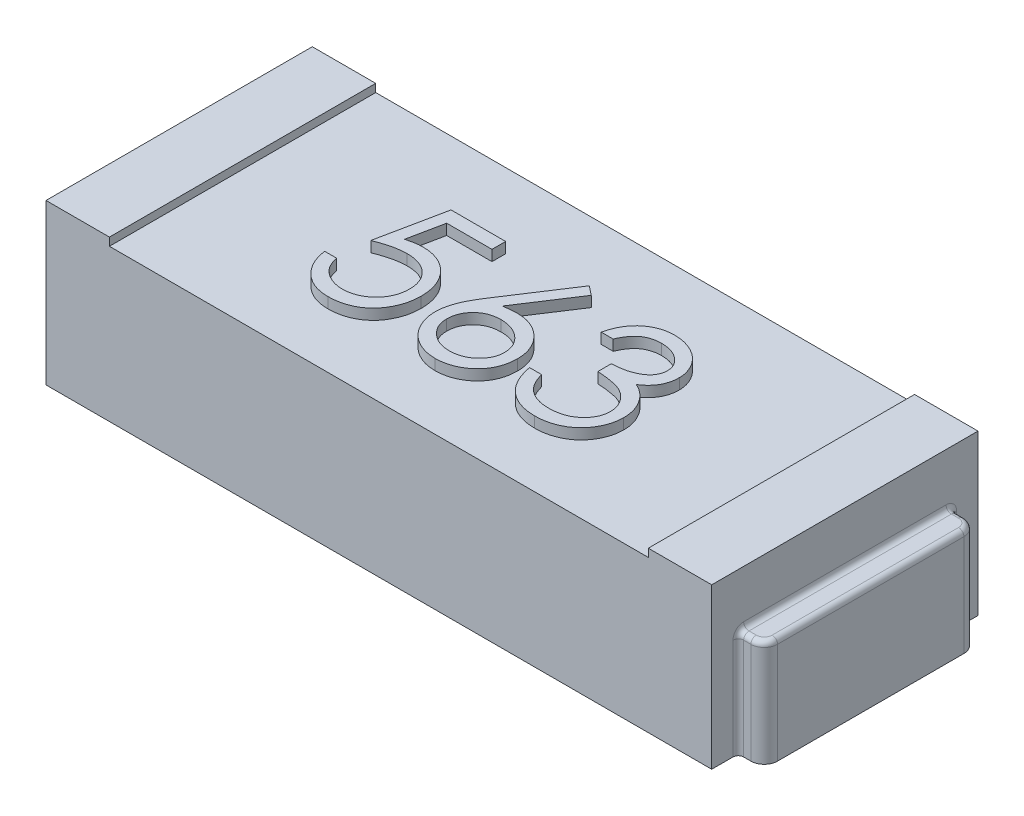
SolidWorks part; units mm, degrees
ref_plane "Plan de face" through (0, 0, 0) normal (0, 0, 1) x (1, 0, 0)
ref_plane "Plan de dessus" through (0, 0, 0) normal (0, 1, 0) x (1, 0, 0)
ref_plane "Plan de droite" through (0, 0, 0) normal (1, 0, 0) x (0, 0, -1)
sketch "Esquisse1" plane through (0, 0, 0) normal (0, 1, 0) x (1, 0, 0)
  line L1 (1.25, -0.5) -> (-1.25, -0.5)
  line L2 (1.25, -0.5) -> (1.25, 0.5)
  line L3 (1.25, 0.5) -> (-1.25, 0.5)
  line L4 (-1.25, -0.5) -> (-1.25, 0.5)
  line L5 (1.25, -0.5) -> (-1.25, 0.5) construction
  line L6 (1.25, 0.5) -> (-1.25, -0.5) construction
  point P0 (0, 0)
  dimension "D1" = 2.5
  dimension "D2" = 1
extrude "Boss.-Extru.1" add sketch "Esquisse1" along normal blind 0.6
sketch "Esquisse2" plane through (0, 0.6, 0) normal (0, 1, 0) x (1, 0, 0)
  line L0 (1.25, 0.5) -> (-1.25, 0.5) construction
  line L1 (1.0118, -0.5) -> (-1.0118, -0.5)
  line L2 (1.0118, -0.5) -> (1.0118, 0.5)
  line L3 (1.0118, 0.5) -> (-1.0118, 0.5)
  line L4 (-1.0118, -0.5) -> (-1.0118, 0.5)
  line L5 (1.0118, -0.5) -> (-1.0118, 0.5) construction
  line L6 (1.0118, 0.5) -> (-1.0118, -0.5) construction
  point P0 (0, 0)
extrude "Enlèv. mat.-Extru.1" cut sketch "Esquisse2" against normal blind 0.03
sketch "Esquisse3" plane through (0, 0, 0) normal (0, 1, 0) x (1, 0, 0)
  line L0 (1.25, -0.5) -> (1.25, 0.5) construction
  line L1 (1.25, 0.4) -> (1.2971, 0.4)
  line L2 (1.25, 0.4) -> (1.25, -0.4)
  line L3 (1.25, -0.4) -> (1.2971, -0.4)
  line L4 (1.3471, 0.35) -> (1.3471, -0.35)
  line L5 (1.25, 0.5) -> (1.0118, 0.5) construction
  line L6 (1.0118, -0.5) -> (1.25, -0.5) construction
  arc A0 (1.2971, -0.4) -> (1.3471, -0.35) centre (1.2971, -0.35) ccw
  arc A1 (1.2971, 0.4) -> (1.3471, 0.35) centre (1.2971, 0.35) cw
  dimension "D1" = 0.05
  dimension "D2" = 0.1
  dimension "D3" = 0.1
extrude "Boss.-Extru.2" add sketch "Esquisse3" along normal blind 0.4
fillet "Congé1" radius 0.02 8 edges at (1.25, 0.2, -0.4) (1.25, 0.2, 0.4) (1.2736, 0.4, -0.4) (1.3325, 0.4, -0.3854) (1.3471, 0.4, 0) (1.3325, 0.4, 0.3854) (1.2736, 0.4, 0.4) (1.25, 0.4, 0)
mirror "Symétrie2" about plane through (0, 0, 0) normal (1, 0, 0) of "Congé1", "Boss.-Extru.2"
sketch "Esquisse4" plane through (0, 0.57, 0) normal (0, 1, 0) x (1, 0, 0)
  line L0 (0.7576, -0.2803) -> (-0.7576, -0.2803) construction
  text T0 "563" font "Century Gothic" height 0.5
  point P3 (0, -0.2803)
extrude "Boss.-Extru.3" add sketch "Esquisse4" along normal blind 0.04
